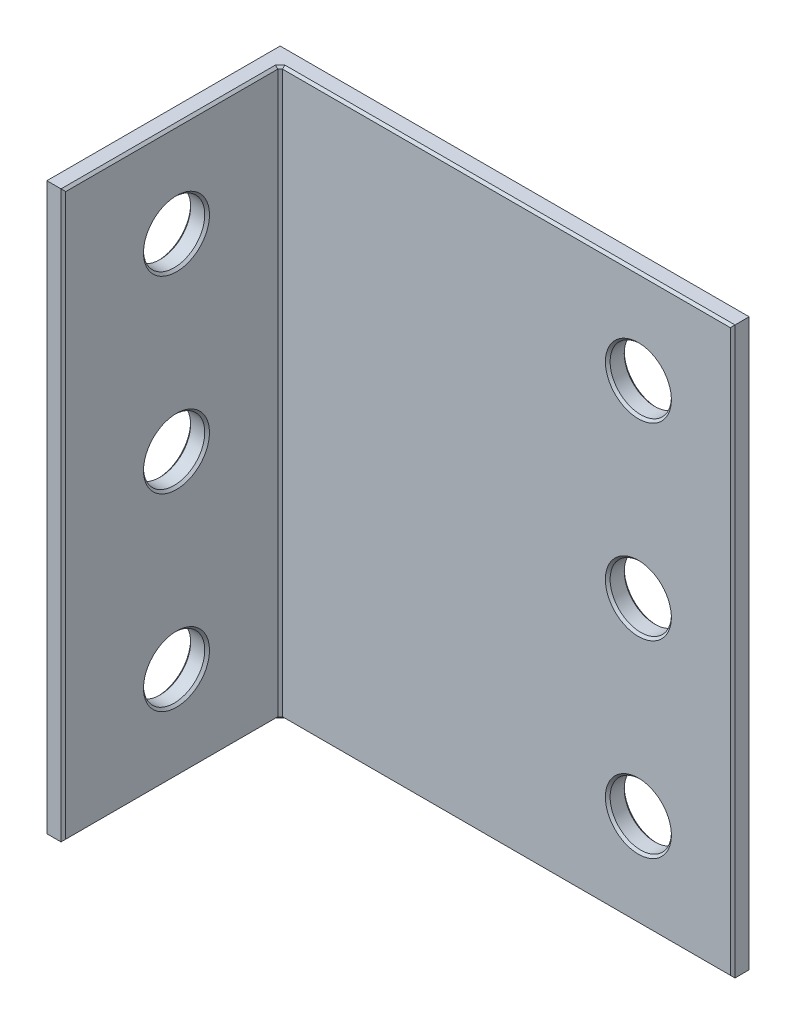
SolidWorks part; units mm, degrees
ref_plane "前视" through (0, 0, 0) normal (0, 0, 1) x (1, 0, 0)
ref_plane "上视" through (0, 0, 0) normal (0, 1, 0) x (1, 0, 0)
ref_plane "右视" through (0, 0, 0) normal (1, 0, 0) x (0, 0, -1)
sketch "草图1" plane through (0, 0, 0) normal (0, 0, 1) x (1, 0, 0)
  line L0 (160, 281.9635) -> (160, -120.4694) construction
  line L1 (0, 0) -> (200, 0)
  line L2 (0, 0) -> (0, 240)
  line L3 (0, 240) -> (200, 240)
  line L4 (200, 0) -> (200, 240)
  circle A0 centre (160, 40) radius 13
  circle A1 centre (160, 120) radius 13
  circle A2 centre (160, 200) radius 13
  dimension "D7" = 26
  dimension "D1" = 240
  dimension "D2" = 200
  dimension "D3" = 160
  dimension "D4" = 40
  dimension "D5" = 80
  dimension "D6" = 80
extrude "基体-拉伸" add sketch "草图1" along normal blind 8
sketch "草图2" plane through (0, 0, 8) normal (0, 0, 1) x (1, 0, 0)
  line L1 (0, 240) -> (8, 240)
  line L2 (0, 240) -> (0, 0)
  line L3 (0, 0) -> (8, 0)
  line L4 (8, 240) -> (8, 0)
  dimension "D1" = 8
extrude "凸台-拉伸1" add sketch "草图2" along normal blind 92
sketch "草图3" plane through (0, 0, 0) normal (-1, 0, 0) x (0, 0, 1)
  line L0 (52, 245.7913) -> (52, 32.4579) construction
  line L1 (0, 240) -> (0, 0) construction
  line L2 (100, 240) -> (0, 240) construction
  circle A0 centre (52, 200) radius 13
  circle A1 centre (52, 120) radius 13
  circle A2 centre (52, 40) radius 13
  dimension "D5" = 26
  dimension "D1" = 52
  dimension "D2" = 40
  dimension "D3" = 80
  dimension "D4" = 80
extrude "切除-拉伸1" cut sketch "草图3" against normal through all
chamfer "倒角1" distance 1 angle 45 26 edges at (173, 200, 0) (173, 40, 0) (173, 120, 0) (173, 120, 8) (173, 40, 8) (173, 200, 8) (100, 0, 0) (200, 120, 0) (100, 240, 0) (0, 240, 50) (0, 120, 100) (0, 0, 50) (0, 120, 0) (0, 200, 65) (0, 120, 65) (0, 40, 65) (104, 240, 8) (200, 120, 8) (104, 0, 8) (8, 0, 54) (8, 120, 100) (8, 240, 54) (8, 120, 8) (8, 187, 52) (8, 107, 52) (8, 27, 52)
